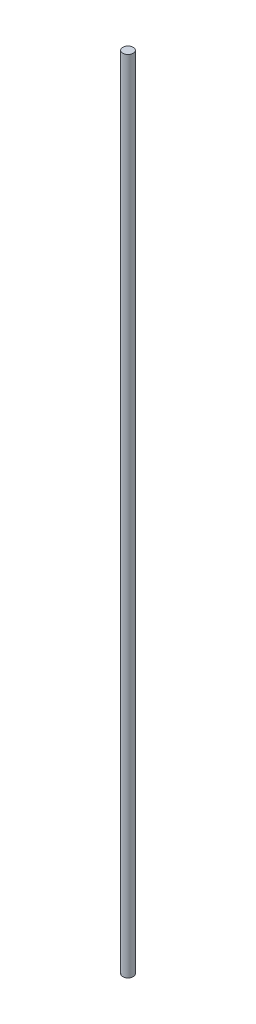
SolidWorks part; units mm, degrees
material "1060 Alloy"
ref_plane "Front Plane" through (0, 0, 0) normal (0, 0, 1) x (1, 0, 0)
ref_plane "Top Plane" through (0, 0, 0) normal (0, 1, 0) x (1, 0, 0)
ref_plane "Right Plane" through (0, 0, 0) normal (1, 0, 0) x (0, 0, -1)
sketch "Sketch1" plane through (0, 0, 0) normal (0, 1, 0) x (1, 0, 0)
  circle A0 centre (0, 0) radius 4.1
  dimension "D1" = 8.2
extrude "Boss-Extrude1" add sketch "Sketch1" along normal blind 628.71
